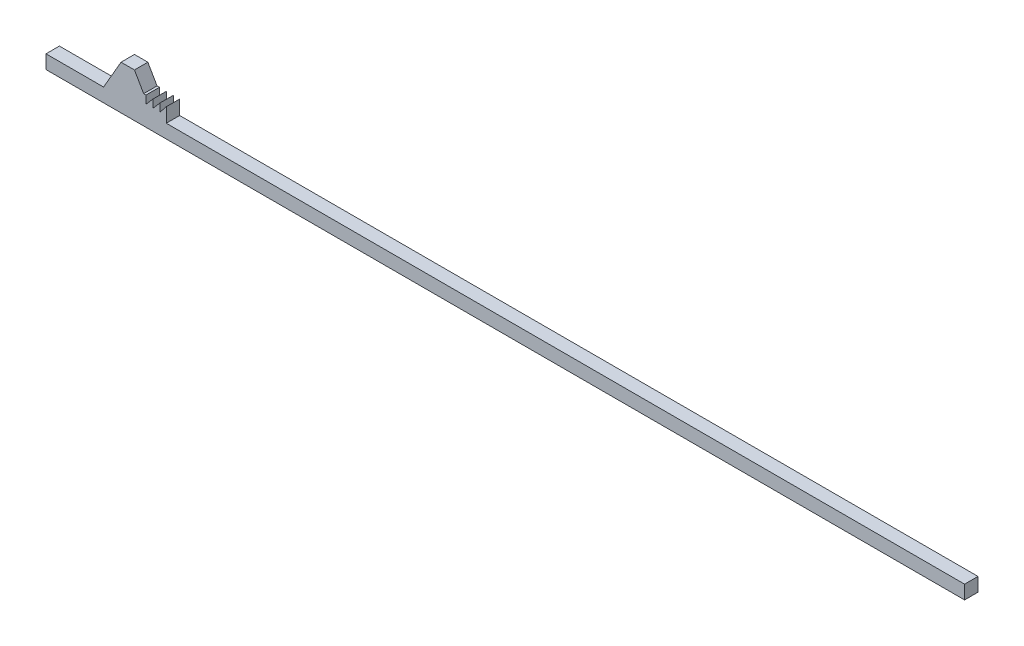
SolidWorks part; units mm, degrees
ref_plane "前视基准面" through (0, 0, 0) normal (0, 0, 1) x (1, 0, 0)
ref_plane "上视基准面" through (0, 0, 0) normal (0, 1, 0) x (1, 0, 0)
ref_plane "右视基准面" through (0, 0, 0) normal (1, 0, 0) x (0, 0, -1)
sketch "Model" plane through (0, 0, 0) normal (0, 0, 1) x (1, 0, 0)
  line L0 (614.2461, 32.4844) -> (617.6765, 26.5428)
  line L1 (581.2813, 21.2098) -> (602.7367, 21.2098)
  line L2 (609.2461, 32.4844) -> (602.7367, 21.2098)
  line L3 (618.5599, 23.568) -> (618.5599, 26.5428)
  line L4 (621.1432, 23.568) -> (621.1432, 26.5428)
  line L5 (621.1432, 26.5428) -> (618.5599, 23.568)
  line L6 (623.7265, 23.568) -> (623.7265, 26.5428)
  line L7 (623.7265, 26.5428) -> (621.1432, 23.568)
  line L8 (623.7265, 23.568) -> (626.1113, 26.5428)
  line L9 (618.5599, 26.5428) -> (617.6765, 26.5428)
  line L10 (581.2813, 16.1098) -> (923.648, 16.1098)
  line L11 (626.1113, 21.2098) -> (923.648, 21.2098)
  line L12 (626.1113, 26.5428) -> (626.1113, 21.2098)
  line L13 (581.2813, 16.1098) -> (581.2813, 21.2098)
  line L14 (923.648, 21.2098) -> (923.648, 16.1098)
  line L15 (609.2461, 32.4844) -> (614.2461, 32.4844)
extrude "凸台-拉伸1" add sketch "Model" along normal blind 5
